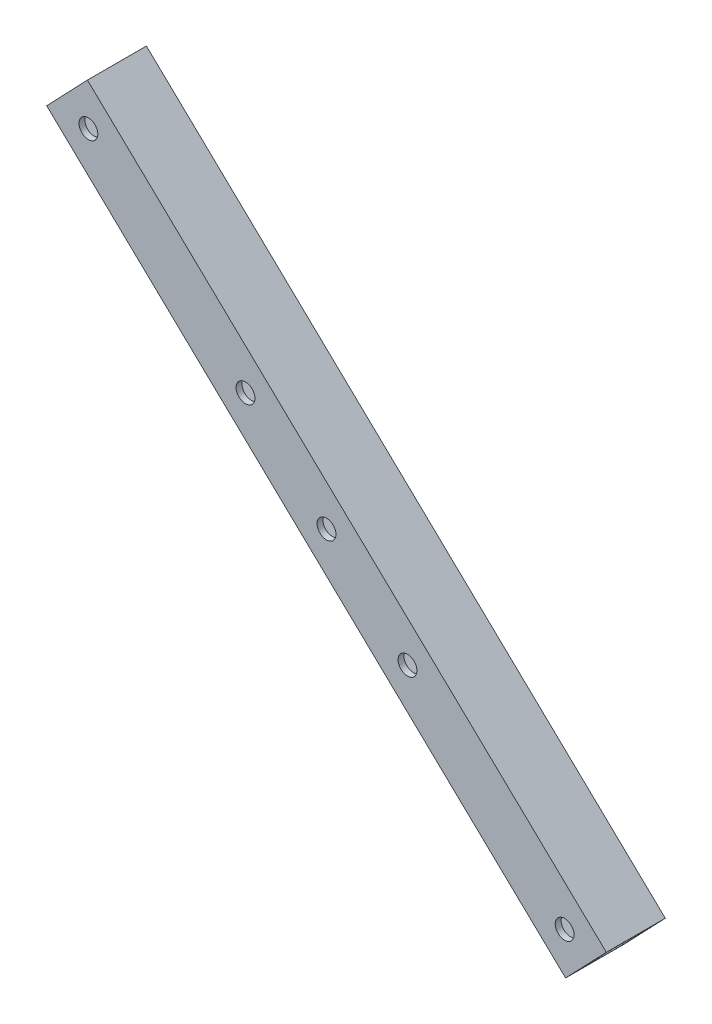
SolidWorks part; units mm, degrees
ref_plane "正面" through (0, 0, 0) normal (0, 0, 1) x (1, 0, 0)
ref_plane "平面" through (0, 0, 0) normal (0, 1, 0) x (1, 0, 0)
ref_plane "右側面" through (0, 0, 0) normal (1, 0, 0) x (0, 0, -1)
sketch "ｽｹｯﾁ2" plane through (0, 0, 0) normal (0, 0, 1) x (1, 0, 0)
  line L0 (-3.7761, 84.2848) -> (76.9904, 7.0917)
  line L1 (83.0716, 8.196) -> (-3.936, 91.3541)
  line L2 (-3.936, 91.3541) -> (-10.8454, 84.1249)
  line L3 (-10.8454, 84.1249) -> (77.1503, 0.0225)
  line L4 (77.1503, 0.0225) -> (84.0597, 7.2517)
  line L5 (84.0597, 7.2517) -> (83.0716, 8.196)
  circle A0 centre (-3.7761, 84.2848) radius 1.6
  circle A1 centre (76.9904, 7.0917) radius 1.6
  dimension "D1" = 111.7229
  dimension "D4" = 5
  dimension "D5" = 5
  dimension "D2" = 5
  dimension "D3" = 5
extrude "ﾎﾞｽ - 押し出し1" add sketch "ｽｹｯﾁ2" along normal blind 10
sketch "ｽｹｯﾁ3" plane through (40.3084, -38.525, 0) normal (0.7229, -0.6909, 0) x (0, 0, -1)
  line L0 (-10, 53.322) -> (0, 53.322) construction
  line L1 (-9, 54.322) -> (-1, 54.322)
  line L2 (-9, 54.322) -> (-9, 62.322)
  line L3 (-9, 62.322) -> (-1, 62.322)
  line L4 (-1, 54.322) -> (-1, 62.322)
  line L5 (-10, 53.322) -> (-10, 63.322) construction
  dimension "D1" = 1
  dimension "D2" = 1
  dimension "D3" = 8
  dimension "D4" = 8
extrude "ｶｯﾄ - 押し出し1" cut sketch "ｽｹｯﾁ3" against normal through all
sketch "ｽｹｯﾁ4" plane through (0, 0, 10) normal (0, 0, 1) x (1, 0, 0)
  line L0 (33.1525, 42.0737) -> (36.6072, 45.6883)
  line L1 (-10.8454, 84.1249) -> (77.1503, 0.0225) construction
  circle A0 centre (50.3426, 32.5605) radius 1.6
  circle A1 centre (22.8717, 58.816) radius 1.6
  circle A2 centre (36.6072, 45.6883) radius 1.6
  dimension "D1" = 19
  dimension "D2" = 19
extrude "ｶｯﾄ - 押し出し2" cut sketch "ｽｹｯﾁ4" against normal blind 10
